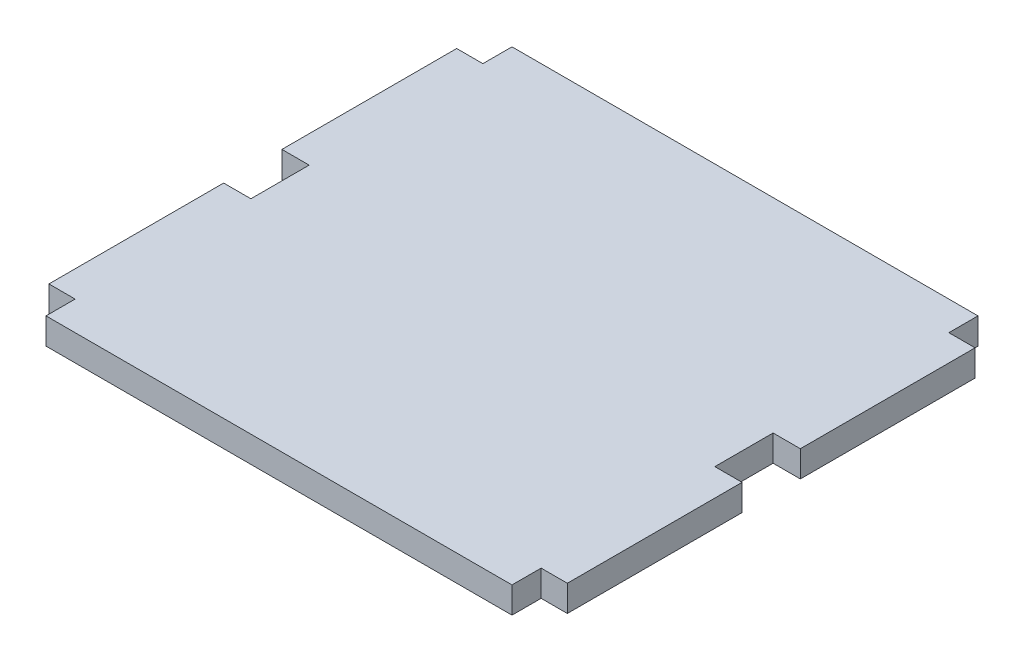
SolidWorks part; units mm, degrees
ref_plane "Front Plane" through (0, 0, 0) normal (0, 0, 1) x (1, 0, 0)
ref_plane "Top Plane" through (0, 0, 0) normal (0, 1, 0) x (1, 0, 0)
ref_plane "Right Plane" through (0, 0, 0) normal (1, 0, 0) x (0, 0, -1)
sketch "Sketch1" plane through (0, 0, 0) normal (0, 1, 0) x (1, 0, 0)
  line L0 (0, 0) -> (0, 50000) construction
  line L1 (-40, -40) -> (40, -40)
  line L2 (-44.5, -35) -> (-44.5, -5)
  line L3 (-40, 40) -> (40, 40)
  line L4 (44.5, -35) -> (44.5, -5)
  line L5 (-40, -35.9551) -> (40, 35.9551) construction
  line L6 (-40, 35.9551) -> (40, -35.9551) construction
  line L7 (44.5, 5) -> (44.5, 35)
  line L8 (44.5, -35) -> (40, -35)
  line L11 (44.5, 35) -> (40, 35)
  line L12 (40, 40) -> (40, 35)
  line L13 (40, -40) -> (39.8241, -40)
  line L14 (44.5, -35) -> (44.5, -32.9179)
  line L16 (39.8241, -40) -> (39.8241, -35.797)
  line L17 (44.5, 5) -> (39.8241, 5)
  line L20 (39.8241, 5) -> (39.8241, 0)
  line L21 (40, -40) -> (40, -35)
  line L24 (39.8241, -5) -> (39.8241, 0)
  line L25 (44.5, -5) -> (39.8241, -5)
  line L27 (-40, -40) -> (-40, -35)
  line L28 (-44.5, -35) -> (-40, -35)
  line L30 (-44.5, 35) -> (-40, 35)
  line L31 (-40, 40) -> (-40, 35)
  line L34 (-44.5, -5) -> (-39.8241, -5)
  line L36 (-44.5, 5) -> (-39.8241, 5)
  line L37 (-39.8241, 5) -> (-39.8241, 0)
  line L38 (-39.8241, -5) -> (-39.8241, 0)
  line L39 (-44.5, 5) -> (-44.5, 35)
  line L40 (-39.8241, 0) -> (39.8241, 0) construction
  point P0 (0, 0)
  dimension "D1" = 89
  dimension "D2" = 80
  dimension "D4" = 4.5
  dimension "D5" = 5
extrude "Boss-Extrude1" add sketch "Sketch1" along normal blind 4.5
